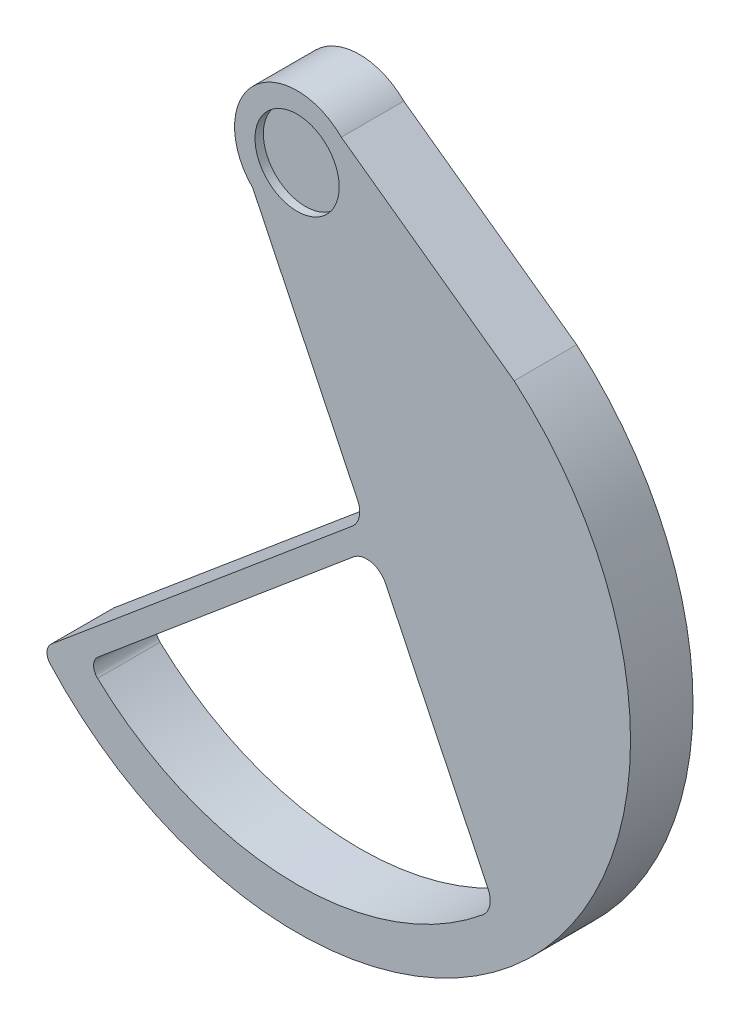
SolidWorks part; units mm, degrees
ref_plane "正面" through (0, 0, 0) normal (0, 0, 1) x (1, 0, 0)
ref_plane "平面" through (0, 0, 0) normal (0, 1, 0) x (1, 0, 0)
ref_plane "右側面" through (0, 0, 0) normal (1, 0, 0) x (0, 0, -1)
sketch "ｽｹｯﾁ4" plane through (0, 0, 0) normal (0, 0, 1) x (1, 0, 0)
  line L0 (0, 0.7897) -> (0, 0)
  line L1 (-53.6231, -124.9951) -> (-58.9406, -129.4571)
  line L3 (-10.6066, -10.6066) -> (14.5363, -62.8896)
  line L4 (-53.6231, -124.9951) -> (13.2442, -68.8868)
  line L5 (21.2324, -76.8138) -> (45.8448, -127.9938)
  line L6 (10.6066, 10.6066) -> (52.0762, -19.2705)
  line L7 (-58.0696, -135.2532) -> (-57.9498, -135.1527)
  line L8 (-47.7477, -126.5866) -> (13.5112, -75.1515)
  arc A1 (-59.2335, -133.7716) -> (52.0762, -19.2705) centre (0, -80) ccw
  arc A2 (-47.8702, -131.073) -> (44.5187, -134.0193) centre (0, -80) ccw
  arc A3 (10.6066, 10.6066) -> (-10.6066, -10.6066) centre (0, 0) ccw
  arc A4 (-59.2335, -133.7716) -> (-58.9406, -129.4571) centre (-57.0123, -131.7552) cw
  arc A5 (-47.8702, -131.073) -> (-47.7477, -126.5866) centre (-45.8186, -128.8841) cw
  arc A6 (13.5112, -75.1515) -> (21.2324, -76.8138) centre (16.7264, -78.9807) cw
  arc A7 (13.2442, -68.8868) -> (14.5363, -62.8896) centre (10.0302, -65.0566) ccw
  arc A8 (45.8448, -127.9938) -> (44.5187, -134.0193) centre (41.3388, -130.1608) cw
  point P18 (-61.2836, -131.423)
  point P21 (-50.2744, -128.7081)
  point P24 (18.4421, -71.0114)
  dimension "D3" = 140
  dimension "D4" = 30
  dimension "D5" = 5
  dimension "D6" = 3
  dimension "D7" = 3
  dimension "D8" = 5
  dimension "D9" = 5
  dimension "D10" = 5
  dimension "D2" = 5
extrude "ﾎﾞｽ - 押し出し1" add sketch "ｽｹｯﾁ4" along normal blind 15
sketch "ｽｹｯﾁ5" plane through (0, 0, 15) normal (0, 0, 1) x (1, 0, 0)
  circle A0 centre (0, 0) radius 10.1
  dimension "D1" = 20.2
extrude "ｶｯﾄ - 押し出し2" cut sketch "ｽｹｯﾁ5" against normal blind 2
